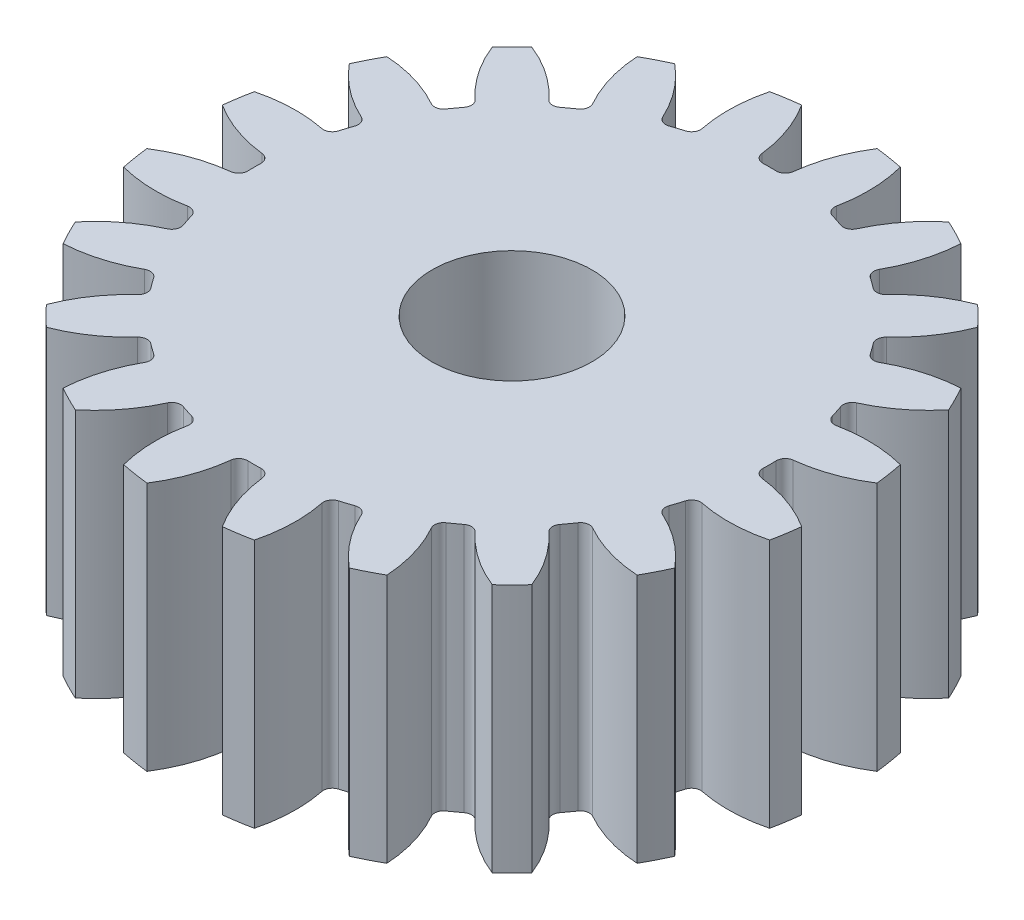
SolidWorks part; units mm, degrees
ref_plane "Ebene vorne" through (0, 0, 0) normal (0, 0, 1) x (1, 0, 0)
ref_plane "Ebene oben" through (0, 0, 0) normal (0, 1, 0) x (1, 0, 0)
ref_plane "Ebene rechts" through (0, 0, 0) normal (1, 0, 0) x (0, 0, -1)
sketch "Skizze1" plane through (0, 0, 0) normal (0, 1, 0) x (1, 0, 0)
  circle A0 centre (0, 0) radius 6
  circle A1 centre (0, 0) radius 1.6
  circle A2 centre (0, 0) radius 6.6
  circle A3 centre (0, 0) radius 5.16
  dimension "D1" = 12
  dimension "D2" = 3.2
  dimension "D3" = 0.6
  dimension "D4" = 1.44
extrude "Aufsatz-Linear austragen1" add sketch "Skizze1" along normal blind 5 contours A3 A1 | A0 A3 | A2 A0
sketch "Skizze2" plane through (0, 5, 0) normal (0, 1, 0) x (1, 0, 0)
  line L0 (0, 0) -> (0, 6.6) construction
  line L1 (-0.4708, 5.9815) -> (0.4708, 5.9815) construction
  line L2 (0, 0) -> (-0.2994, 5.1513) construction
  line L3 (0, 4.6881) -> (-0.7534, 6.7581) construction
  line L4 (0, 0) -> (1.0325, 6.5187) construction
  line L5 (0.4708, 5.9815) -> (1.4007, 5.8342) construction
  circle A0 centre (0, 0) radius 6 construction
  arc A1 (-0.8841, 6.7423) -> (-0.2994, 5.1513) centre (-3.2177, 4.9817) cw
  arc A2 (0.8841, 6.7423) -> (0.2994, 5.1513) centre (3.2177, 4.9817) ccw
  circle A3 centre (0, 0) radius 5.16 construction
  arc A4 (-0.2994, 5.1513) -> (0.2994, 5.1513) centre (0, 0) cw
  circle A5 centre (0, 0) radius 6.6 construction
  arc A6 (0.8841, 6.7423) -> (-0.8841, 6.7423) centre (0, 0) ccw
  dimension "D1" = 6.8
  dimension "D2" = 20
  dimension "D3" = 9
extrude "Schnitt-Linear austragen1" cut sketch "Skizze2" against normal through all
fillet "Verrundung1" radius 0.18 2 edges at (0.2994, 2.5, -5.1513) (-0.2994, 2.5, -5.1513)
pattern_circular "Kreismuster1" count 20 over 360 about axis through (0, 0, 0) along (0, 1, 0) of "Schnitt-Linear austragen1", "Verrundung1"
equation "\"Tooth\"= 20"
equation "\"Module\"= 0.6mm"
equation "\"D1@Skizze1\"=\"Module\"*\"Tooth\""
equation "\"D3@Skizze1\"=\"Module\""
equation "\"D4@Skizze1\"=\"Module\"*if(\"Module\" => 1.25,2.25,2.4)"
equation "\"D3@Skizze2\"=180/\"Tooth\""
